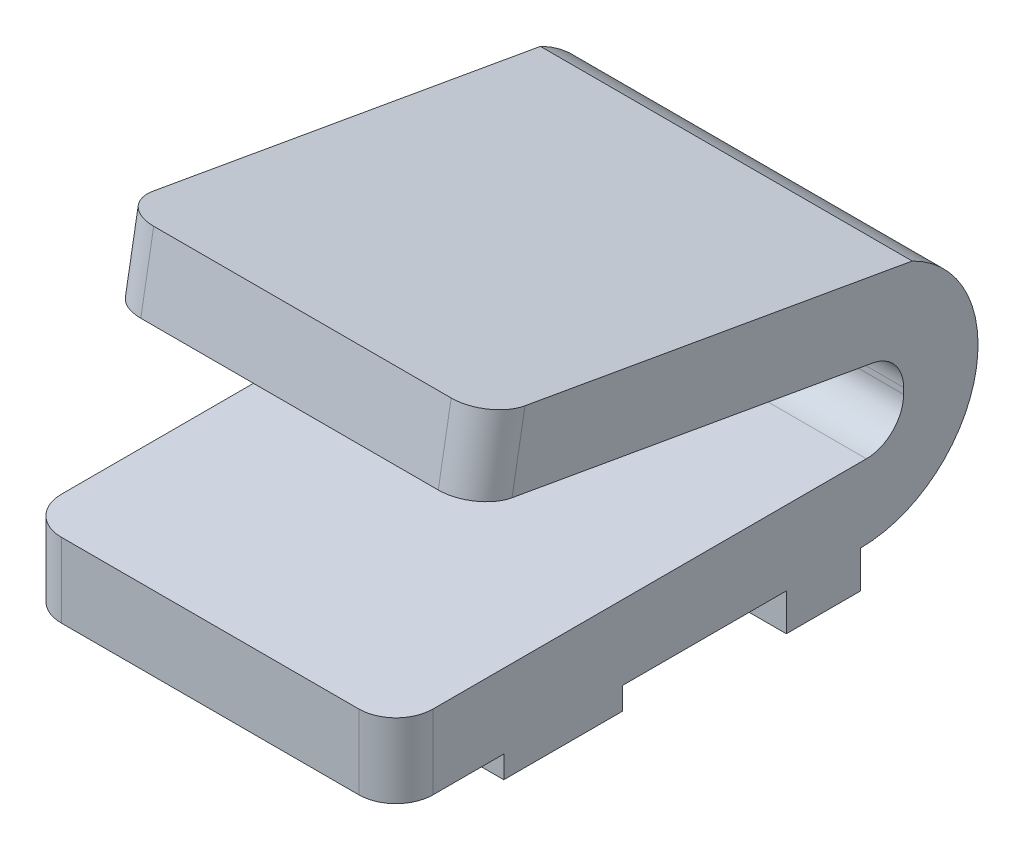
SolidWorks part; units mm, degrees
ref_plane "Front Plane" through (0, 0, 0) normal (0, 0, 1) x (1, 0, 0)
ref_plane "Top Plane" through (0, 0, 0) normal (0, 1, 0) x (1, 0, 0)
ref_plane "Right Plane" through (0, 0, 0) normal (1, 0, 0) x (0, 0, -1)
sketch "Sketch1" plane through (0, 0, 0) normal (1, 0, 0) x (0, 0, -1)
  line L0 (-4, 3.6) -> (-4, 0) construction
  line L1 (0, 0) -> (-6.25, 0)
  line L2 (0, 0) -> (0, 3.1171)
  line L3 (0, 3.1171) -> (0.6929, 2.9949)
  line L4 (-6.25, 0) -> (-6.25, 1)
  line L5 (-6.25, 1) -> (0.0764, 1)
  line L6 (0, 0) -> (-1, 0)
  line L7 (0, 0) -> (0, -0.5)
  line L8 (0, -0.5) -> (-1, -0.5)
  line L9 (-1, 0) -> (-1, -0.5)
  line L10 (-4.8, 0) -> (-3.2, 0)
  line L11 (-4.8, 0) -> (-4.8, -0.3)
  line L12 (-4.8, -0.3) -> (-3.2, -0.3)
  line L13 (-3.2, 0) -> (-3.2, -0.3)
  line L14 (0.5764, 1.5) -> (0.5764, 1.5805)
  line L15 (0.1632, 2.0729) -> (-5.181, 3.0152)
  line L16 (-5.181, 3.0152) -> (-5.0074, 4)
  line L17 (-5.0074, 4) -> (0, 3.1171)
  arc A0 (0.5764, 1.5805) -> (0.1632, 2.0729) centre (0.0764, 1.5805) ccw
  arc A1 (0.0764, 1) -> (0.5764, 1.5) centre (0.0764, 1.5) ccw
  arc A2 (0, 0) -> (0.6929, 2.9949) centre (0, 1.5776) ccw
  point P17 (0.5764, 2)
  point P23 (0.5764, 1)
  point P26 (1.537, 1.222)
  dimension "D12" = 0.5
  dimension "D1" = 2.25
  dimension "D2" = 1
  dimension "D3" = 3
  dimension "D4" = 1.6
  dimension "D5" = 0.3
  dimension "D6" = 0.5
  dimension "D7" = 1
  dimension "D8" = 1
  dimension "D9" = 10
  dimension "D10" = 1
  dimension "D11" = 4
  dimension "D13" = 1
extrude "Boss-Extrude1" add sketch "Sketch1" along normal blind 5
sketch "Sketch2" plane through (0, -0.3, 0) normal (0, -1, 0) x (1, 0, 0)
  line L0 (5, 4.8) -> (0, 4.8) construction
  line L1 (1.7, 4.8) -> (3.3, 4.8)
  line L2 (1.7, 4.8) -> (1.7, 3.2)
  line L3 (1.7, 3.2) -> (3.3, 3.2)
  line L4 (3.3, 4.8) -> (3.3, 3.2)
  line L5 (5, 3.2) -> (0, 3.2) construction
  line L6 (0, 4.8) -> (0, 3.2) construction
  line L7 (5, 4.8) -> (5, 3.2) construction
  dimension "D1" = 1.7
  dimension "D2" = 1.7
extrude "Cut-Extrude1" cut sketch "Sketch2" against normal up to surface (0.3 mm away) up to face at (2.5, 0, 5.525)
fillet "Fillet1" radius 0.5 4 edges at (0, 0.5, 6.25) (5, 0.5, 6.25) (0, 3.5076, 5.0942) (5, 3.5076, 5.0942)
